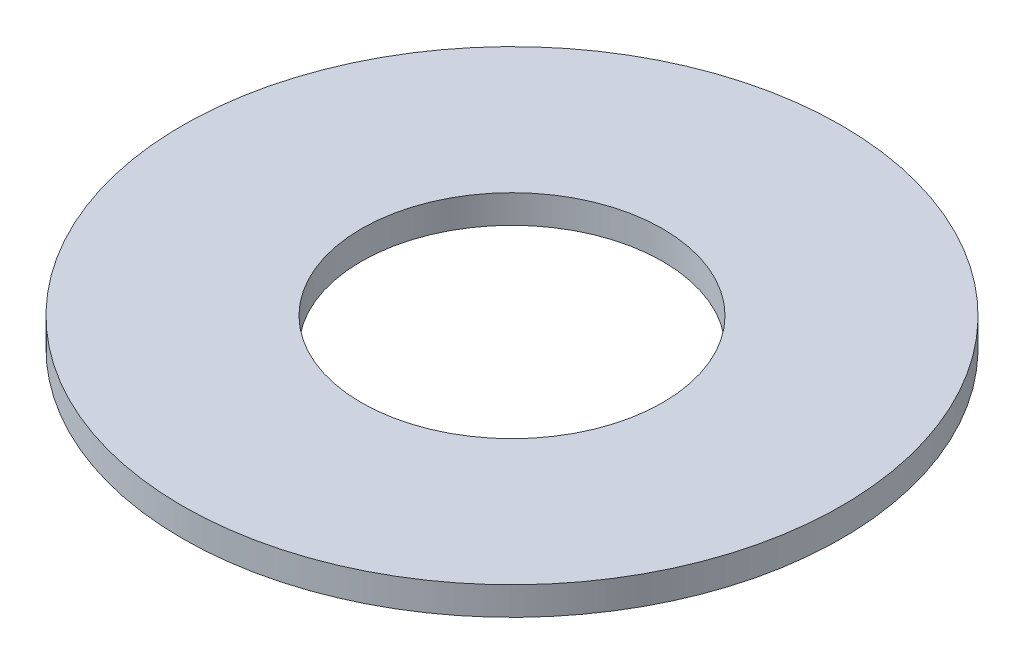
SolidWorks part; units mm, degrees
ref_plane "Plan de face" through (0, 0, 0) normal (0, 0, 1) x (1, 0, 0)
ref_plane "Plan de dessus" through (0, 0, 0) normal (0, 1, 0) x (1, 0, 0)
ref_plane "Plan de droite" through (0, 0, 0) normal (1, 0, 0) x (0, 0, -1)
sketch "Sketch1" plane through (0, 0, 0) normal (0, 1, 0) x (1, 0, 0)
  circle A0 centre (0, 0) radius 3.5
extrude "Boss-Extrude1" add sketch "Sketch1" along normal blind 0.3
sketch "Sketch2" plane through (0, 0.3, 0) normal (0, 1, 0) x (-1, 0, 0)
  circle A0 centre (0, 0) radius 1.6
extrude "Cut-Extrude1" cut sketch "Sketch2" against normal through all
